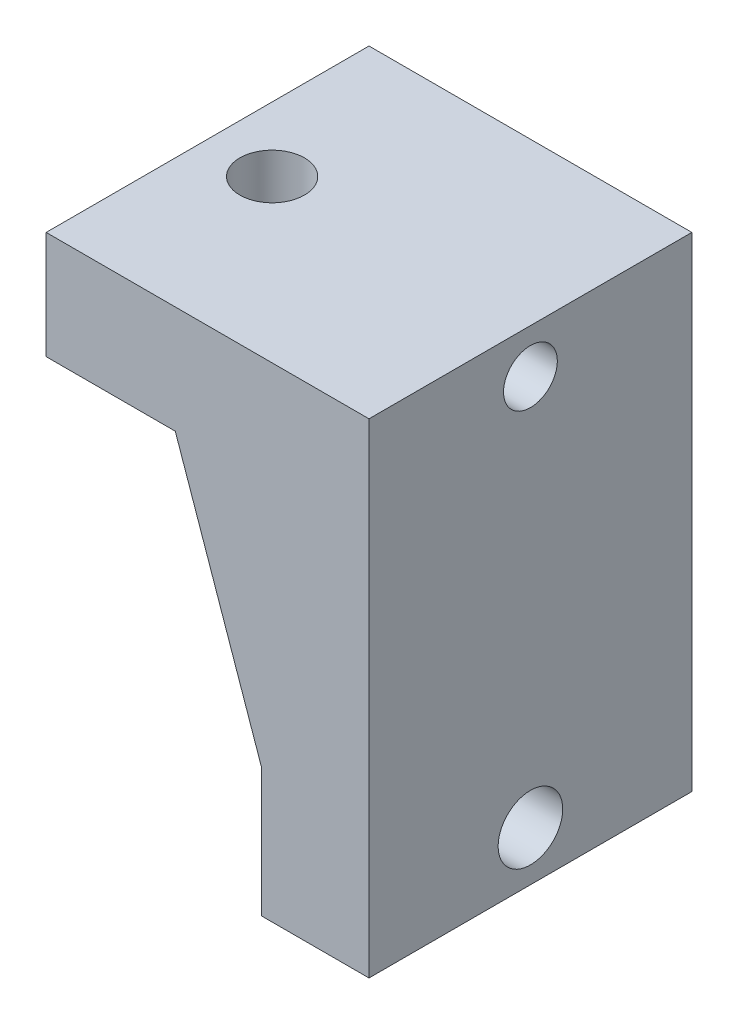
SolidWorks part; units mm, degrees
ref_plane "Ebene vorne" through (0, 0, 0) normal (0, 0, 1) x (1, 0, 0)
ref_plane "Ebene oben" through (0, 0, 0) normal (0, 1, 0) x (1, 0, 0)
ref_plane "Ebene rechts" through (0, 0, 0) normal (1, 0, 0) x (0, 0, -1)
sketch "Skizze1" plane through (0, 0, 0) normal (0, 0, 1) x (1, 0, 0)
  line L0 (-1.5, -2.5) -> (2.5, -14)
  line L1 (-7.5, -2.5) -> (7.5, -2.5)
  line L2 (-7.5, -2.5) -> (-7.5, 2.5)
  line L3 (-7.5, 2.5) -> (7.5, 2.5)
  line L4 (7.5, -2.5) -> (7.5, 2.5)
  line L5 (-7.5, -2.5) -> (7.5, 2.5) construction
  line L6 (-7.5, 2.5) -> (7.5, -2.5) construction
  line L7 (7.5, 2.5) -> (2.5, 2.5)
  line L8 (7.5, 2.5) -> (7.5, -20)
  line L9 (7.5, -20) -> (2.5, -20)
  line L10 (2.5, 2.5) -> (2.5, -20)
  line L11 (-5.9162, -20) -> (2.5, -20)
  point P0 (0, 0)
  dimension "D1" = 15
  dimension "D2" = 5
  dimension "D3" = 5
  dimension "D4" = 22.5
  dimension "D5" = 6
  dimension "D6" = 6
extrude "Aufsatz-Linear austragen1" add sketch "Skizze1" along normal blind 15 contours L10 L3 L2 L1 | L3 L10 L1 L4 | L10 L1 L0 | L1 L10 L9 L8
sketch "Skizze2" plane through (7.5, 0, 0) normal (1, 0, 0) x (0, 0, -1)
  line L0 (-15, -20) -> (-15, 2.5) construction
  line L1 (-15, -20) -> (0, -20) construction
  line L2 (-15, 2.5) -> (0, 2.5) construction
  circle A0 centre (-7.5, 0.45) radius 1.25
  circle A1 centre (-7.5, -17.7) radius 1.5
  dimension "D3" = 2.5
  dimension "D4" = 3
  dimension "D1" = 7.5
  dimension "D2" = 7.5
  dimension "D5" = 2.3
  dimension "D6" = 2.05
extrude "Schnitt-Linear austragen1" cut sketch "Skizze2" against normal blind 9
sketch "Skizze3" plane through (0, -2.5, 0) normal (0, -1, 0) x (1, 0, 0)
  line L0 (-7.5, 15) -> (-1.5, 15) construction
  line L1 (-7.5, 15) -> (-7.5, 0) construction
  line L2 (7.5, 15) -> (7.5, 0) construction
  circle A0 centre (-4.5, 7.5) radius 1.5
  dimension "D2" = 3
  dimension "D1" = 7.5
  dimension "D3" = 3
  dimension "D4" = 12
extrude "Schnitt-Linear austragen2" cut sketch "Skizze3" against normal blind 9
